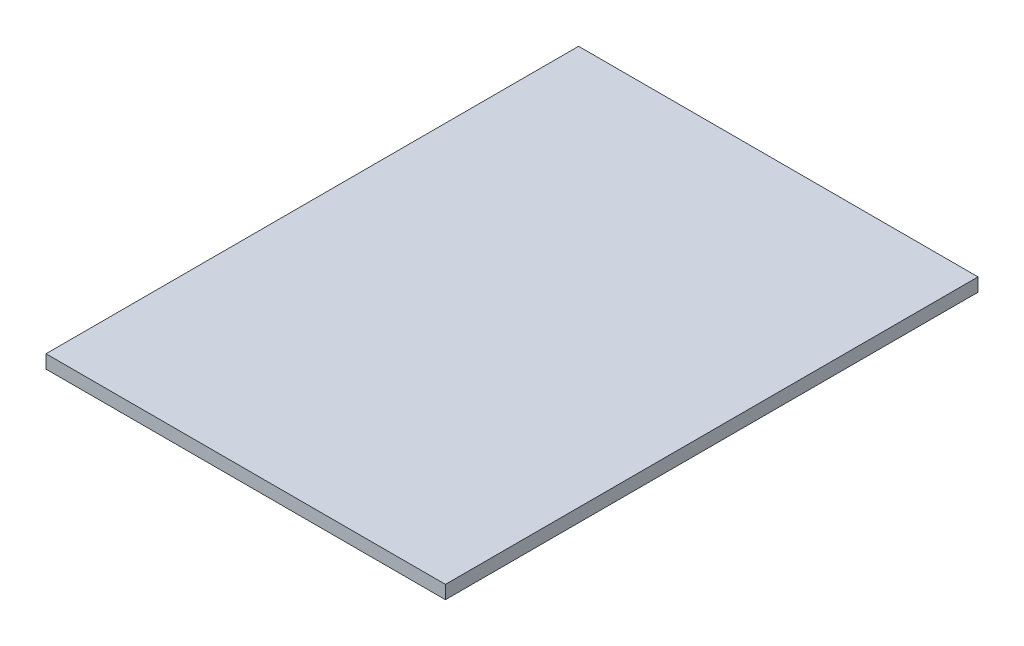
SolidWorks part; units mm, degrees
ref_plane "Front Plane" through (0, 0, 0) normal (0, 0, 1) x (1, 0, 0)
ref_plane "Top Plane" through (0, 0, 0) normal (0, 1, 0) x (1, 0, 0)
ref_plane "Right Plane" through (0, 0, 0) normal (1, 0, 0) x (0, 0, -1)
sketch "Esquisse1" plane through (0, 0, 0) normal (0, 1, 0) x (1, 0, 0)
  line L1 (0, 0) -> (600, 0)
  line L2 (0, 0) -> (0, 800)
  line L3 (0, 800) -> (600, 800)
  line L4 (600, 0) -> (600, 800)
  dimension "D1" = 600
  dimension "D2" = 800
extrude "Boss.-Extru.1" add sketch "Esquisse1" along normal blind 20
